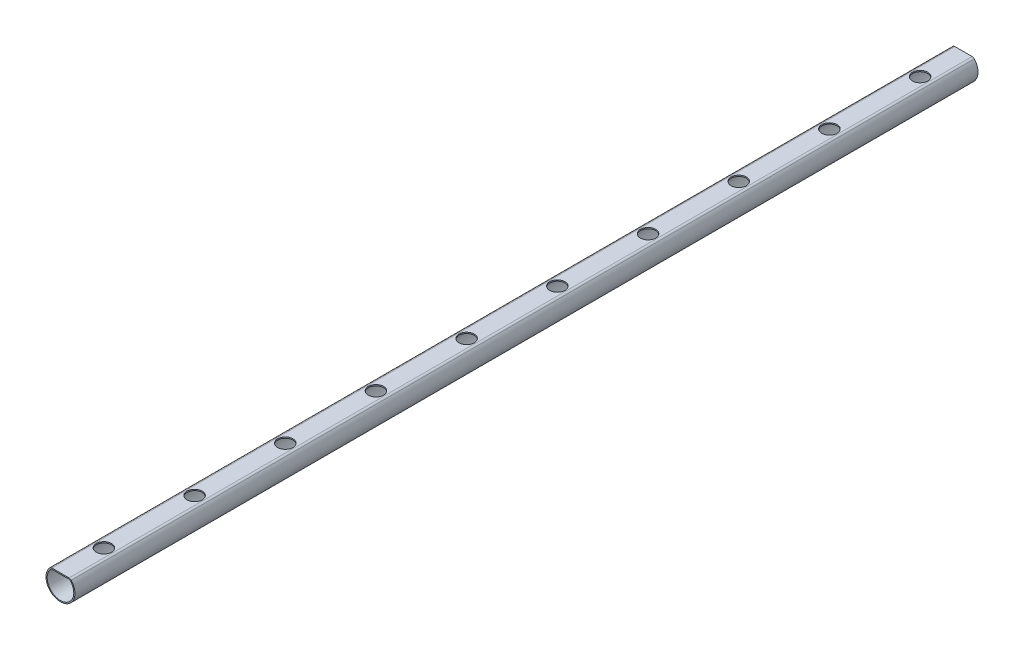
SolidWorks part; units mm, degrees
ref_plane "Front Plane" through (0, 0, 0) normal (0, 0, 1) x (1, 0, 0)
ref_plane "Top Plane" through (0, 0, 0) normal (0, 1, 0) x (1, 0, 0)
ref_plane "Right Plane" through (0, 0, 0) normal (1, 0, 0) x (0, 0, -1)
sketch "Sketch1" plane through (0, 0, 0) normal (0, 0, 1) x (1, 0, 0)
  line L0 (8.9443, 11) -> (-8.9443, 11)
  line L1 (8.9443, 9.8) -> (-8.9443, 9.8)
  arc A0 (-11.1803, 10) -> (11.1803, 10) centre (0, 0) ccw
  arc A1 (-11.1803, 10) -> (-8.9443, 11) centre (-8.9443, 8) cw
  arc A2 (8.9443, 11) -> (11.1803, 10) centre (8.9443, 8) cw
  arc A3 (-10.2859, 9.2) -> (10.2859, 9.2) centre (0, 0) ccw
  arc A4 (8.9443, 9.8) -> (10.2859, 9.2) centre (8.9443, 8) cw
  arc A5 (-10.2859, 9.2) -> (-8.9443, 9.8) centre (-8.9443, 8) cw
  dimension "D1" = 30
  dimension "D3" = 3
  dimension "D2" = 11
  dimension "D4" = 1.2
extrude "Boss-Extrude1" add sketch "Sketch1" along normal blind 936
sketch "Sketch2" plane through (0, 11, 0) normal (0, 1, 0) x (1, 0, 0)
  line L0 (0, 0) -> (0, -936) construction
  line L1 (8.9443, -936) -> (-8.9443, -936) construction
  circle A0 centre (0, -891) radius 7.9
  circle A1 centre (0, -797) radius 7.9
  circle A2 centre (0, -703) radius 7.9
  circle A3 centre (0, -609) radius 7.9
  circle A4 centre (0, -515) radius 7.9
  circle A5 centre (0, -421) radius 7.9
  circle A6 centre (0, -327) radius 7.9
  circle A7 centre (0, -233) radius 7.9
  circle A8 centre (0, -139) radius 7.9
  circle A9 centre (0, -45) radius 7.9
  dimension "D1" = 15.8
  dimension "D2" = 45
  dimension "D3" = 10
extrude "Cut-Extrude1" cut sketch "Sketch2" against normal up to next
pattern_linear "LPattern1" [suppressed] count 2 spacing 940
